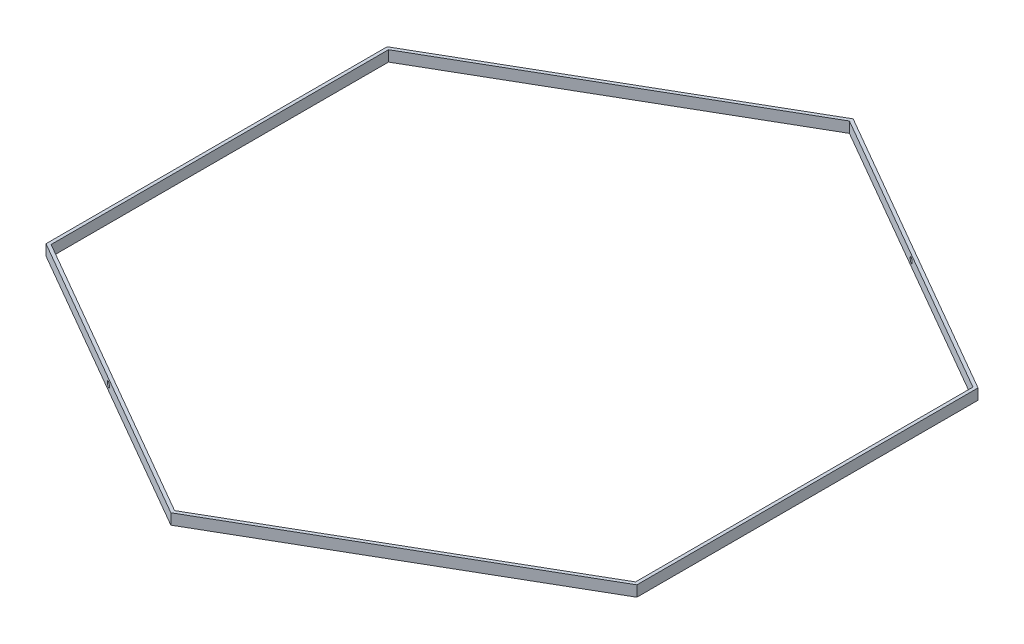
SolidWorks part; units mm, degrees
ref_plane "Plano frontal" through (0, 0, 0) normal (0, 0, 1) x (1, 0, 0)
ref_plane "Plano superior" through (0, 0, 0) normal (0, 1, 0) x (1, 0, 0)
ref_plane "Plano direito" through (0, 0, 0) normal (1, 0, 0) x (0, 0, -1)
sketch "Esboço1" plane through (0, 0, 0) normal (0, 1, 0) x (1, 0, 0)
  line L0 (110, -63.5085) -> (110, 63.5085)
  line L1 (110, 63.5085) -> (0, 127.0171)
  line L2 (0, 127.0171) -> (-110, 63.5085)
  line L3 (-110, 63.5085) -> (-110, -63.5085)
  line L4 (-110, -63.5085) -> (0, -127.0171)
  line L5 (0, -127.0171) -> (110, -63.5085)
  line L6 (108.8, 62.8157) -> (0, 125.6314)
  line L7 (0, 125.6314) -> (-108.8, 62.8157)
  line L8 (-108.8, 62.8157) -> (-108.8, -62.8157)
  line L9 (-108.8, -62.8157) -> (0, -125.6314)
  line L10 (0, -125.6314) -> (108.8, -62.8157)
  line L11 (108.8, -62.8157) -> (108.8, 62.8157)
  circle A0 centre (0, 0) radius 110 construction
  dimension "D1" = 220
  dimension "D2" = 1.2
extrude "Ressalto-extrusão1" add sketch "Esboço1" along normal blind 4
sketch "Esboço2" plane through (-55, 0, 95.2628) normal (-0.5, 0, 0.866) x (0.866, 0, 0.5)
  line L0 (-63.5085, 2) -> (0, 2) construction
  line L1 (-63.5085, 4) -> (-63.5085, 0) construction
  line L2 (0, 2) -> (63.5085, 2) construction
  line L3 (63.5085, 4) -> (63.5085, 0) construction
  circle A0 centre (0, 2) radius 1
  dimension "D1" = 2
extrude "Corte-extrusão1" cut sketch "Esboço2" against normal through all
